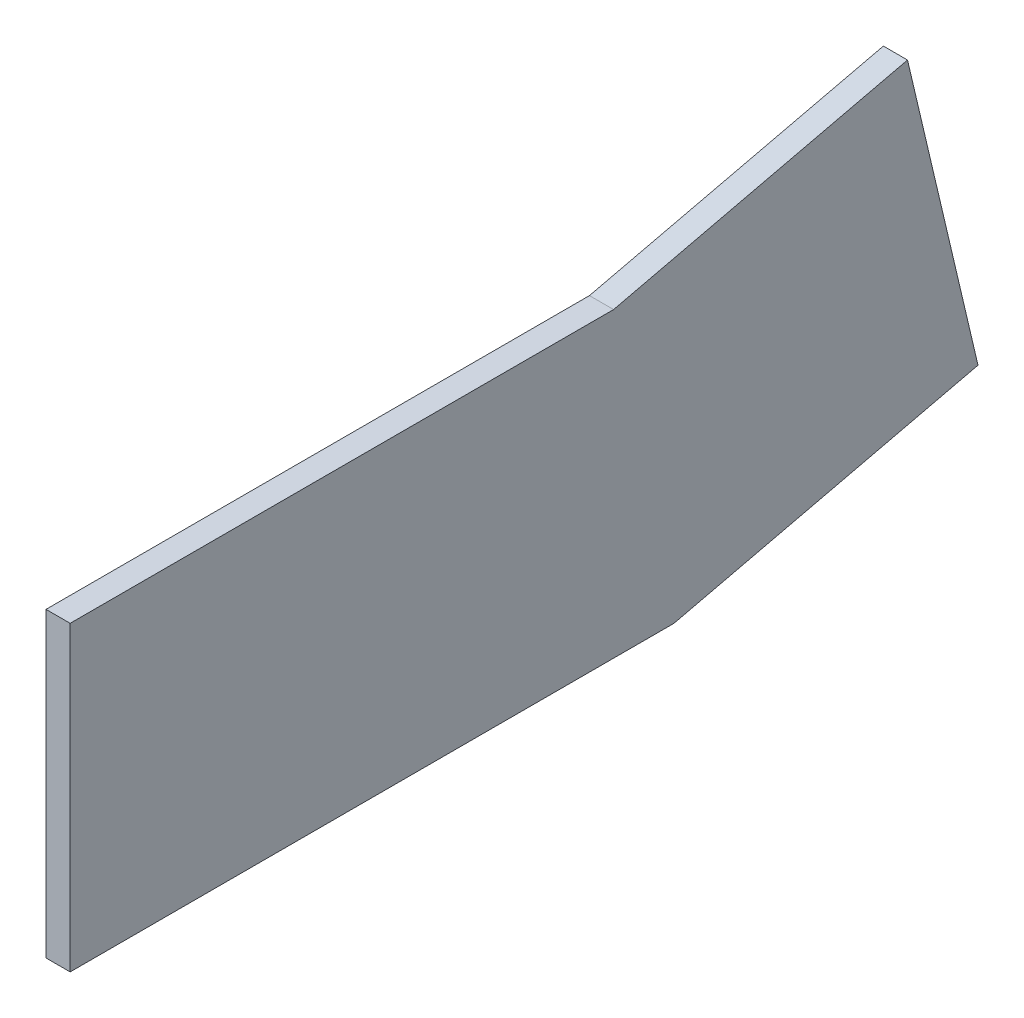
SolidWorks part; units mm, degrees
ref_plane "Front Plane" through (0, 0, 0) normal (0, 0, 1) x (1, 0, 0)
ref_plane "Top Plane" through (0, 0, 0) normal (0, 1, 0) x (1, 0, 0)
ref_plane "Right Plane" through (0, 0, 0) normal (1, 0, 0) x (0, 0, -1)
sketch "Sketch1" plane through (0, 0, 0) normal (1, 0, 0) x (0, 0, -1)
  line L0 (-148.1697, -40) -> (21.8303, -40) construction
  line L1 (21.8303, -40) -> (21.8303, 0) construction
  line L2 (21.8303, 0) -> (-148.1697, -40) construction
  line L3 (0, 0) -> (-25.1715, -5.9227)
  line L4 (-25.1715, -5.9227) -> (-75.1715, -5.9227)
  line L5 (-75.1715, -5.9227) -> (-75.1715, 19.0773)
  line L6 (-75.1715, 19.0773) -> (-30.1715, 19.0773)
  line L8 (-30.1715, 19.0773) -> (-5.8361, 24.8033)
  line L9 (-5.8361, 24.8033) -> (0, 0)
  point P2 (0, 0)
  point P11 (0, 0)
  point P12 (0, 0)
  point P14 (0, 0)
  point P15 (0, 0)
  dimension "D1" = 170
  dimension "D2" = 40
  dimension "D3" = 25
  dimension "D4" = 25
  dimension "D5" = 50
  dimension "D6" = 5
  dimension "D7" = 45
extrude "Boss-Extrude1" add sketch "Sketch1" along normal blind 2
